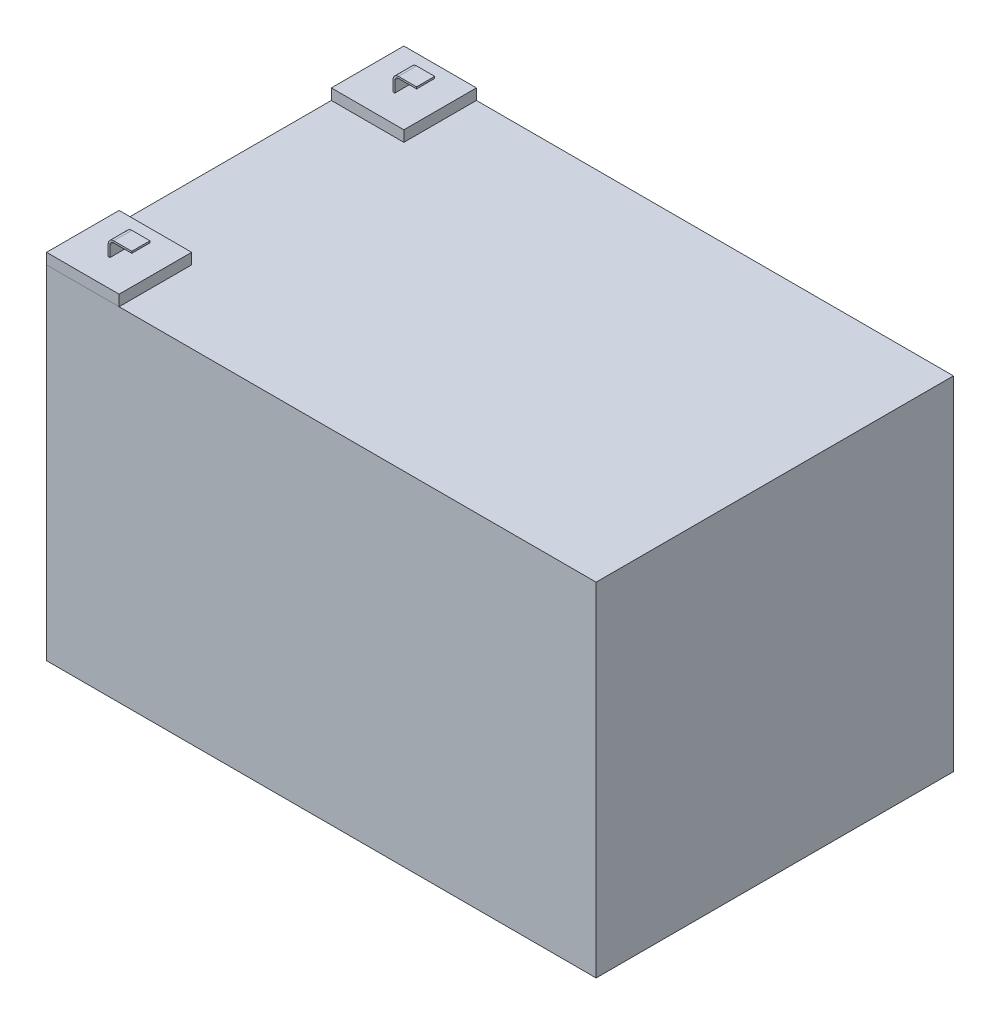
SolidWorks part; units mm, degrees
material "PBT General Purpose"
ref_plane "Front Plane" through (0, 0, 0) normal (0, 0, 1) x (1, 0, 0)
ref_plane "Top Plane" through (0, 0, 0) normal (0, 1, 0) x (1, 0, 0)
ref_plane "Right Plane" through (0, 0, 0) normal (1, 0, 0) x (0, 0, -1)
sketch "Sketch1" plane through (0, 0, 0) normal (0, 1, 0) x (1, 0, 0)
  line L1 (75.75, 49.25) -> (-75.75, 49.25)
  line L2 (75.75, 49.25) -> (75.75, -49.25)
  line L3 (75.75, -49.25) -> (-75.75, -49.25)
  line L4 (-75.75, 49.25) -> (-75.75, -49.25)
  line L5 (0, -49.25) -> (0, 49.25) construction
  line L6 (75.75, 0) -> (-75.75, 0) construction
  point P0 (0, 0)
  dimension "D1" = 98.5
  dimension "D2" = 151.5
extrude "Boss-Extrude1" add sketch "Sketch1" along normal blind 94.5
sketch "Sketch2" plane through (0, 94.5, 0) normal (0, 1, 0) x (1, 0, 0)
  line L0 (-75.75, 0) -> (75.75, 0) construction
  line L1 (-75.75, 49.25) -> (-75.75, -49.25) construction
  line L2 (75.75, -49.25) -> (75.75, 49.25) construction
  line L3 (-75.75, 49.25) -> (-75.75, 29.25)
  line L4 (-75.75, -49.25) -> (-55.75, -49.25)
  line L5 (-75.75, -49.25) -> (-75.75, -29.25)
  line L6 (-75.75, -29.25) -> (-55.75, -29.25)
  line L7 (-55.75, -49.25) -> (-55.75, -29.25)
  line L8 (-65.75, -29.25) -> (-65.75, -49.25) construction
  line L9 (-75.75, -39.25) -> (-55.75, -39.25) construction
  line L10 (-75.75, 49.25) -> (-55.75, 49.25)
  line L11 (-55.75, 49.25) -> (-55.75, 29.25)
  line L12 (-75.75, 29.25) -> (-55.75, 29.25)
  point P170 (-65.75, -39.25)
  dimension "D1" = 20
  dimension "D2" = 20
extrude "Boss-Extrude2" add sketch "Sketch2" along normal blind 3 separate body
ref_plane "Plane1" through (0, 0, 39.25) normal (0, 0, 1) x (1, 0, 0)
sketch "Sketch3" plane through (0, 0, 39.25) normal (0, 0, 1) x (1, 0, 0)
  line L0 (-65.75, 97.5) -> (-65.75, 100.5)
  line L1 (-75.75, 97.5) -> (-55.75, 97.5) construction
  line L2 (-64.75, 101.5) -> (-59.75, 101.5)
  line L3 (-66.25, 97.5) -> (-66.25, 100.5)
  line L4 (-64.75, 102) -> (-59.75, 102)
  line L5 (-59.75, 102) -> (-59.75, 101.5)
  line L6 (-65.75, 97.5) -> (-66.25, 97.5)
  arc A0 (-65.75, 100.5) -> (-64.75, 101.5) centre (-64.75, 100.5) cw
  arc A1 (-66.25, 100.5) -> (-64.75, 102) centre (-64.75, 100.5) cw
  dimension "D3" = 1.5
  dimension "D2" = 3
  dimension "D4" = 5
  dimension "D1" = 0.5
extrude "Boss-Extrude3" add sketch "Sketch3" along normal blind 2.5 and the other way blind 2.5 separate body
mirror "Mirror2" about plane through (0, 0, 0) normal (0, 0, 1) of bodies 104
